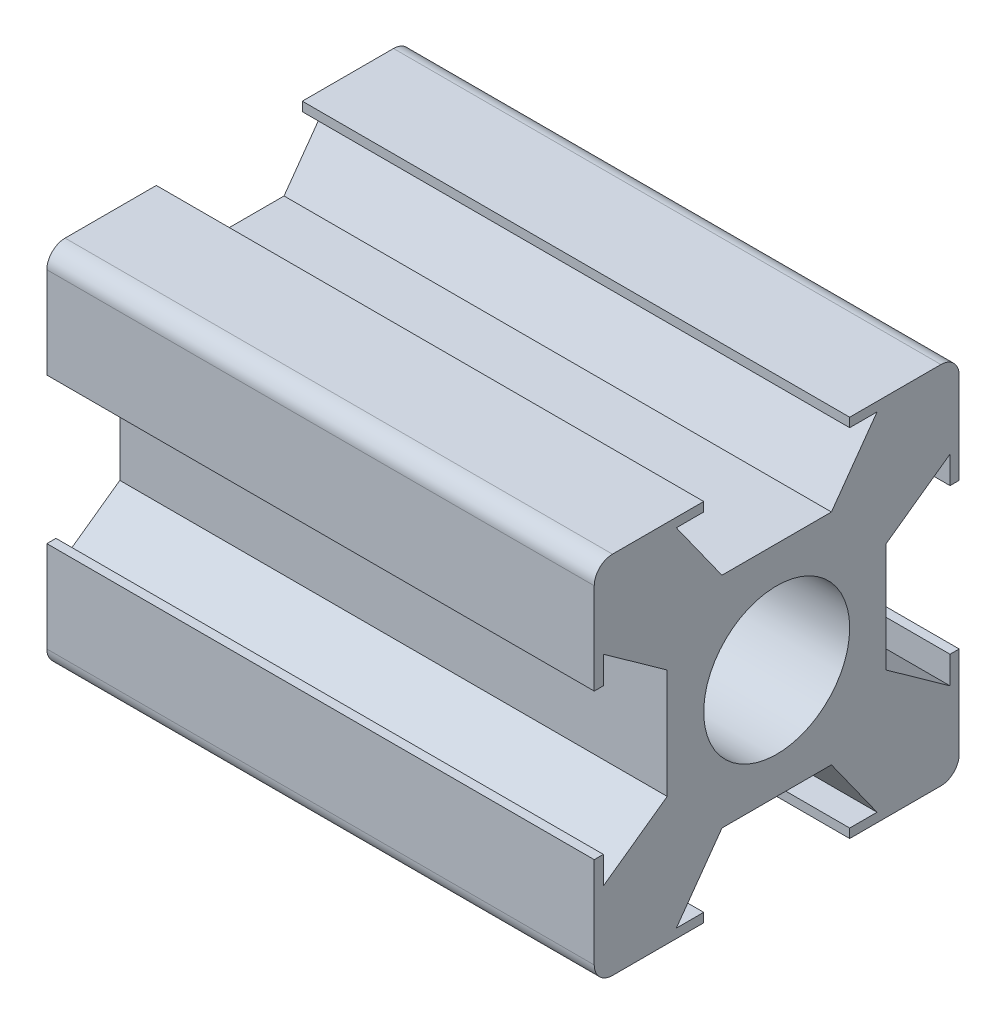
SolidWorks part; units mm, degrees
ref_plane "前视基准面" through (0, 0, 0) normal (0, 0, 1) x (1, 0, 0)
ref_plane "上视基准面" through (0, 0, 0) normal (0, 1, 0) x (1, 0, 0)
ref_plane "右视基准面" through (0, 0, 0) normal (1, 0, 0) x (0, 0, -1)
sketch "草图1" plane through (0, 0, 0) normal (0, 0, 1) x (1, 0, 0)
  line L1 (-66.5187, -1.3979) -> (-36.5187, -1.3979)
  line L2 (-66.5187, -1.3979) -> (-66.5187, -11.3979)
  line L3 (-66.5187, -11.3979) -> (-36.5187, -11.3979)
  line L4 (-36.5187, -1.3979) -> (-36.5187, -11.3979)
  dimension "D1" = 10
  dimension "D2" = 30
extrude "凸台-拉伸1" add sketch "草图1" along normal blind 10
sketch "草图2" plane through (-36.5187, 0, 0) normal (1, 0, 0) x (0, 0, -1)
  circle A0 centre (0, -11.3979) radius 4
  dimension "D1" = 8
extrude "切除-拉伸1" cut sketch "草图2" against normal blind 1270
sketch "草图3" plane through (-36.5187, 0, 0) normal (1, 0, 0) x (0, 0, -1)
  line L0 (-4, -1.3979) -> (0, -1.3979)
  line L1 (-10, -11.3979) -> (-10, -1.3979) construction
  line L2 (-10, -1.3979) -> (0, -1.3979) construction
  line L3 (-10, -7.3979) -> (-10, -11.3979)
  line L4 (-4, -1.3979) -> (-4, -1.8979)
  line L5 (-4, -1.8979) -> (-5.5, -1.8979)
  line L6 (-3, -5.3979) -> (0, -5.3979)
  line L7 (0, -7.3979) -> (0, -1.3979) construction
  line L8 (0, -5.3979) -> (0, -1.3979)
  line L9 (-10, -11.3979) -> (-6, -11.3979)
  line L10 (-10, -11.3979) -> (-4, -11.3979) construction
  line L11 (-6, -11.3979) -> (-6, -8.3979)
  line L12 (-10, -7.3979) -> (-9.5, -7.3979)
  line L13 (-9.5, -7.3979) -> (-9.5, -5.8979)
  line L14 (-5.5, -1.8979) -> (-3, -5.3979)
  line L15 (-9.5, -5.8979) -> (-6, -8.3979)
  dimension "D1" = 4
  dimension "D2" = 4
  dimension "D3" = 4
  dimension "D4" = 4
  dimension "D5" = 0.5
  dimension "D6" = 0.5
  dimension "D7" = 3
  dimension "D8" = 3
  dimension "D9" = 1.5
  dimension "D10" = 1.5
extrude "切除-拉伸2" cut sketch "草图3" against normal blind 1270
fillet "圆角1" radius 1 1 edges at (-51.5187, -1.3979, 10)
pattern_circular "阵列(圆周)2" count 4 over 360 about axis through (0, -11.3979, 0) along (1, 0, 0) of "凸台-拉伸1", "圆角1", "切除-拉伸1", "切除-拉伸2"
